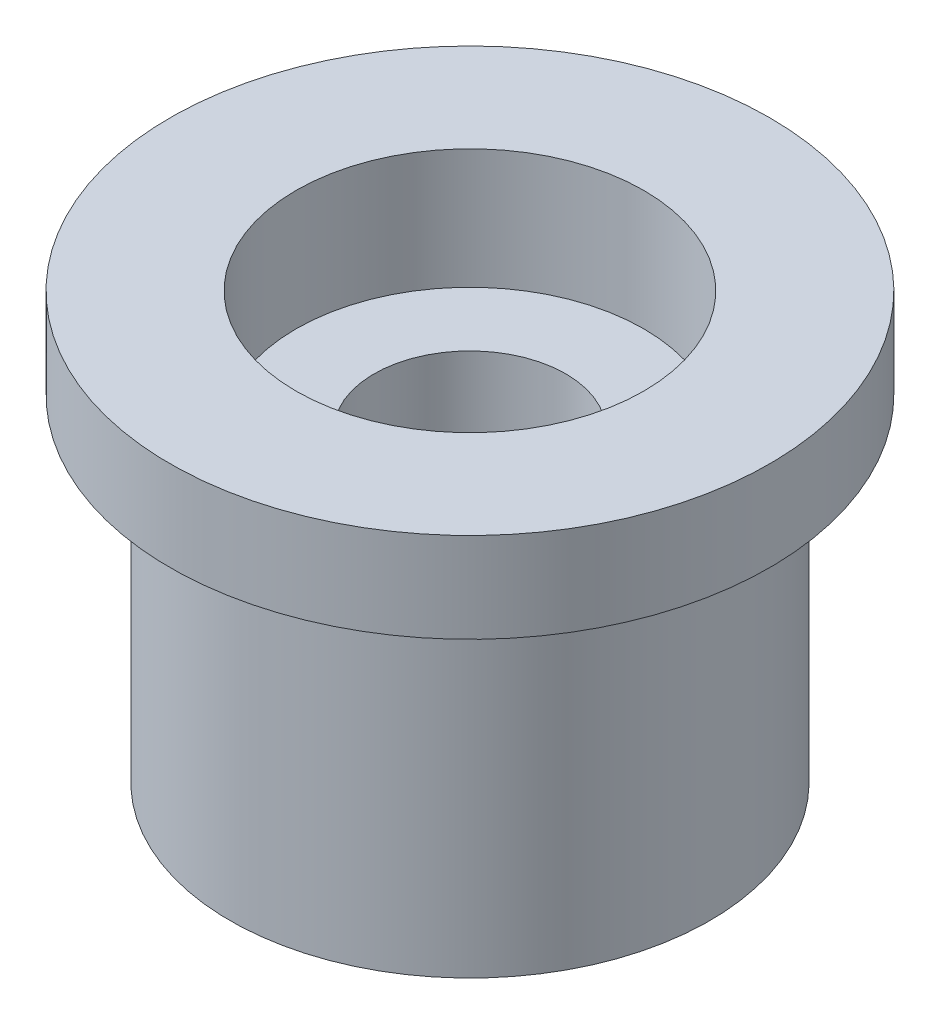
SolidWorks part; units mm, degrees
ref_plane "Front" through (0, 0, 0) normal (0, 0, 1) x (1, 0, 0)
ref_plane "Top" through (0, 0, 0) normal (0, 1, 0) x (1, 0, 0)
ref_plane "Right" through (0, 0, 0) normal (1, 0, 0) x (0, 0, -1)
sketch "Sketch2" plane through (0, 0, 0) normal (0, 0, 1) x (1, 0, 0)
  line L0 (-1.6, 0) -> (-4, 0)
  line L1 (-4, 0) -> (-4, 5.6)
  line L2 (-4, 5.6) -> (-5, 5.6)
  line L3 (-5, 5.6) -> (-5, 7.1)
  line L4 (-5, 7.1) -> (-2.9, 7.1)
  line L5 (-2.9, 7.1) -> (-2.9, 5.1)
  line L6 (-2.9, 5.1) -> (-1.6, 5.1)
  line L7 (-1.6, 5.1) -> (-1.6, 0)
  line L8 (0, 0) -> (0, 16.5894) construction
  dimension "D1" = 10
  dimension "D2" = 8
  dimension "D3" = 2.9
  dimension "D4" = 1.6
  dimension "D5" = 1.5
  dimension "D6" = 2
  dimension "D7" = 7.1
revolve "Revolve2" add sketch "Sketch2" angle 360 about L8
